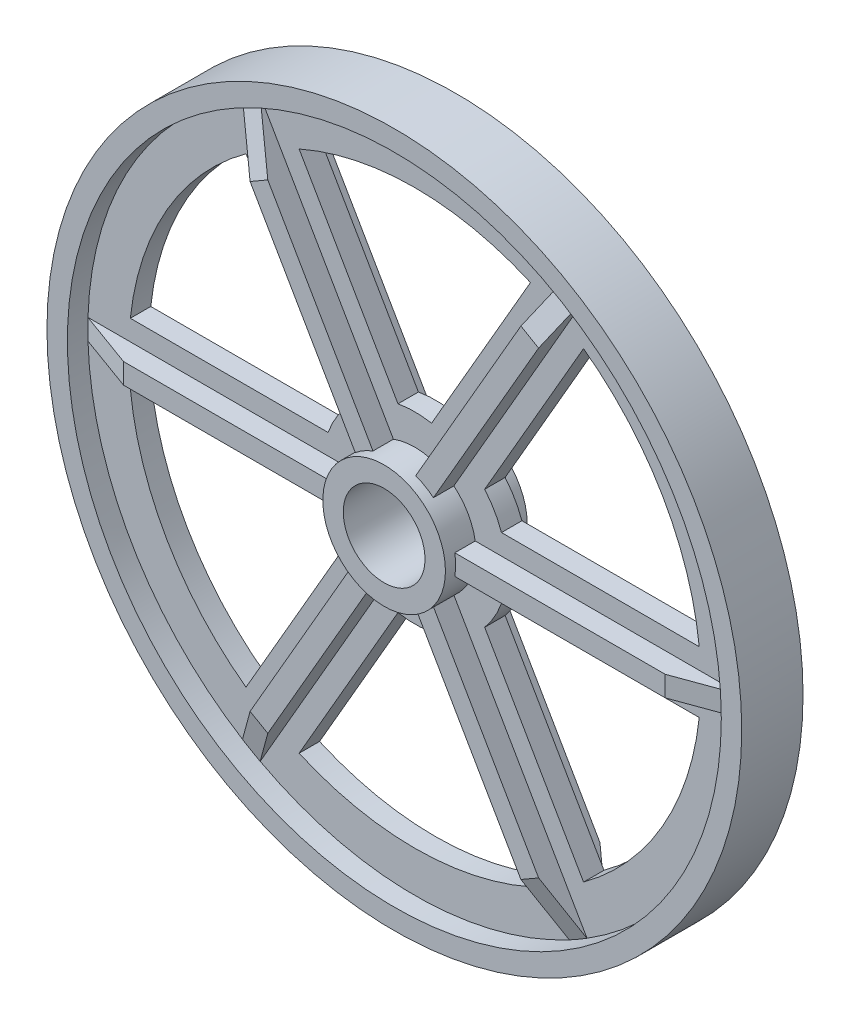
SolidWorks part; units mm, degrees
ref_plane "Front Plane" through (0, 0, 0) normal (0, 0, 1) x (1, 0, 0)
ref_plane "Top Plane" through (0, 0, 0) normal (0, 1, 0) x (1, 0, 0)
ref_plane "Right Plane" through (0, 0, 0) normal (1, 0, 0) x (0, 0, -1)
sketch "Sketch1" plane through (0, 0, 0) normal (0, 0, 1) x (1, 0, 0)
  circle A0 centre (0, 0) radius 15
  dimension "D1" = 30
extrude "Boss-Extrude1" add sketch "Sketch1" along normal mid plane 20 contours A0
sketch "Sketch2" plane through (0, 0, 0) normal (1, 0, 0) x (0, 0, -1)
  line L0 (0, 0) -> (0, 40.1331) construction
  line L1 (-2.5, 15) -> (-2.5, 80)
  line L2 (10, 15) -> (-10, 15) construction
  line L3 (-2.5, 80) -> (-7.5, 80)
  line L4 (-7.5, 80) -> (-7.5, 85)
  line L5 (-7.5, 85) -> (7.5, 85)
  line L6 (7.5, 80) -> (7.5, 85)
  line L7 (2.5, 80) -> (7.5, 80)
  line L8 (2.5, 15) -> (2.5, 80)
  line L9 (0, 0) -> (38.6129, 0) construction
  line L10 (-2.5, 15) -> (2.5, 15)
  point P12 (0, 85)
  dimension "D1" = 15
  dimension "D2" = 5
  dimension "D3" = 5
  dimension "D4" = 70
revolve "Revolve1" add sketch "Sketch2" angle 360 about L9
sketch "Sketch3" plane through (0, 0, 10) normal (0, 0, 1) x (1, 0, 0)
  circle A0 centre (0, 0) radius 10
  dimension "D1" = 20
sketch "Sketch5" plane through (0, 0, 0) normal (0, 1, 0) x (1, 0, 0)
  line L0 (-85, 0) -> (85, 0) construction
  line L1 (-85, 7.5) -> (-85, -7.5) construction
  line L2 (85, -7.5) -> (85, 7.5) construction
  line L3 (0, -2.5) -> (-80, -2.5)
  line L4 (-80, -2.5) -> (80, -2.5) construction
  line L5 (-80, -2.5) -> (-80, -7.5) construction
  line L6 (0, 7.5) -> (-66.2626, 7.5)
  line L7 (0, -2.5) -> (0, -7.5)
  line L8 (-66.2626, 7.5) -> (-80, 2.5)
  line L9 (0, -7.5) -> (-66.2626, -7.5)
  line L10 (-85, -7.5) -> (85, -7.5) construction
  line L11 (-66.2626, -7.5) -> (-80, -2.5)
  line L12 (0, 2.5) -> (-80, 2.5)
  line L13 (0, 2.5) -> (0, 7.5)
  point P8 (0, 0)
  point P9 (0, 0)
  point P10 (0, 0)
  point P13 (0, 0)
  point P14 (-79.4853, -2.5)
  point P22 (0, 0)
  point P23 (0, 0)
  dimension "D1" = 160
extrude "Boss-Extrude9" add sketch "Sketch5" along normal mid plane 5
pattern_circular "CirPattern1" count 6 over 360 about axis through (0, 0, 0) along (0, 0, 1) of "Boss-Extrude9"
sketch "Sketch6" plane through (0, 0, 2.5) normal (0, 0, 1) x (1, 0, 0)
  line L0 (-17.1018, 14.6212) -> (-41.2937, 56.5228)
  line L1 (-69.5971, 7.5) -> (-21.2132, 7.5)
  line L2 (-14.7902, 2.5) -> (-79.9609, 2.5) construction
  line L3 (-42.1455, 67.9982) -> (-9.5602, 11.5587) construction
  arc A0 (-17.1018, 14.6212) -> (-21.2132, 7.5) centre (0, 0) ccw
  arc A1 (-41.2937, 56.5228) -> (-69.5971, 7.5) centre (0, 0) ccw
  dimension "D2" = 70
  dimension "D3" = 22.5
  dimension "D1" = 60
  dimension "D4" = 5
  dimension "D5" = 5
extrude "Cut-Extrude2" cut sketch "Sketch6" against normal blind 5
pattern_circular "CirPattern2" count 6 over 360 about axis through (0, 0, 0) along (0, 0, 1) of "Cut-Extrude2"
extrude "Cut-Extrude3" cut sketch "Sketch3" against normal blind 25
